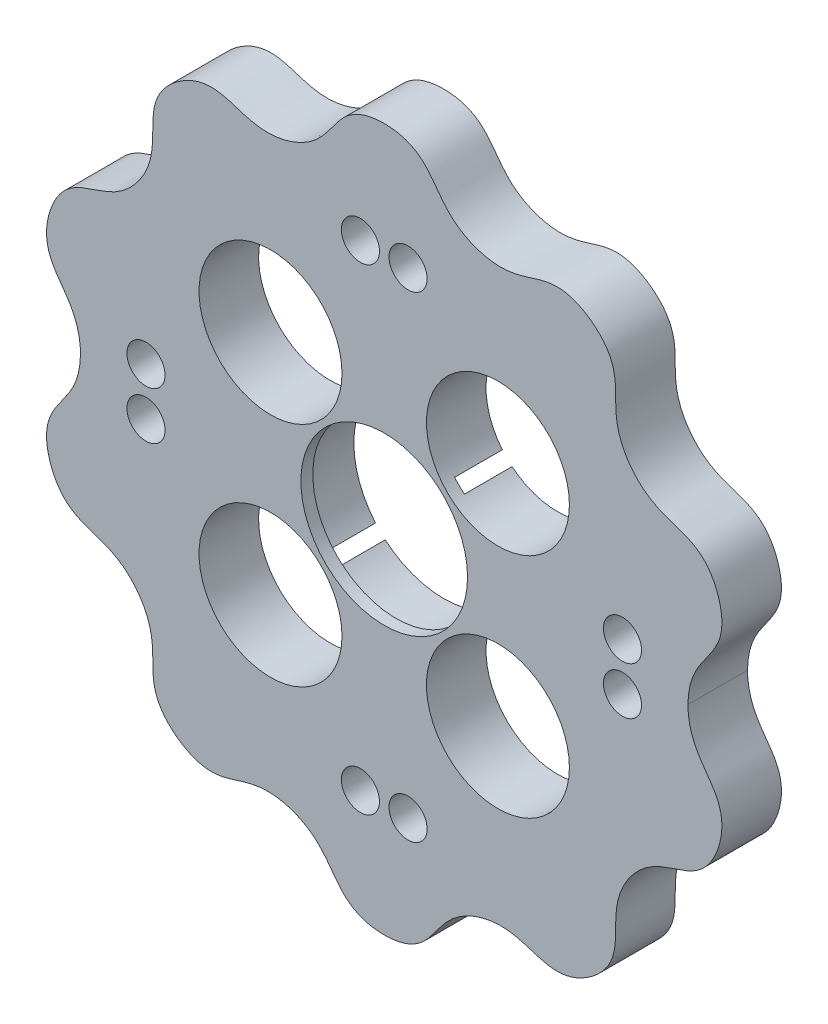
SolidWorks part; units mm, degrees
material "ABS"
ref_plane "Front Plane" through (0, 0, 0) normal (0, 0, 1) x (1, 0, 0)
ref_plane "Top Plane" through (0, 0, 0) normal (0, 1, 0) x (1, 0, 0)
ref_plane "Right Plane" through (0, 0, 0) normal (1, 0, 0) x (0, 0, -1)
ref_plane "Plane1" through (0, 0, 4) normal (0, 0, 1) x (1, 0, 0)
sketch "Sketch3" plane through (0, 0, 4) normal (0, 0, 1) x (1, 0, 0)
  circle A0 centre (2, 0) radius 7.5
  spline S0 degree 5 poles (-23.5, 0) (-23.5, -0.6619) (-23.5985, -1.4561) (-23.8874, -2.4734) (-24.5265, -3.4803) (-25.3239, -4.5428) (-25.7599, -5.1922) (-26.203, -6.107) (-26.3992, -6.9747) (-26.3685, -8.1757) (-26.0322, -9.4106) (-25.4671, -10.5179) (-24.8895, -11.2256) (-23.9802, -11.9083) (-23.1576, -12.2723) (-21.7572, -12.687) (-20.1242, -13.2676) (-18.7699, -14.5833) (-17.7259, -16.1905) (-17.3933, -18.0022) (-17.4393, -19.3418) (-17.4288, -20.3924) (-17.2271, -21.518) (-16.8759, -22.3353) (-16.145, -23.2889) (-15.1471, -24.0902) (-14.0391, -24.6539) (-13.1558, -24.8869) (-12.0189, -24.9048) (-11.1394, -24.7158) (-9.7628, -24.2281) (-8.1004, -23.738) (-6.2314, -24.0063) (-4.442, -24.693) (-3.1081, -25.9632) (-2.3579, -27.074) (-1.7319, -27.9177) (-0.9071, -28.7098) (-0.1425, -29.1646) (1.0093, -29.5065) (2.2876, -29.5682) (3.5153, -29.373) (4.3668, -29.0423) (5.2971, -28.3885) (5.8976, -27.7187) (6.7246, -26.515) (7.7814, -25.1413) (9.4513, -24.2598) (11.3025, -23.7636) (13.1282, -24.0071) (14.3881, -24.4648) (15.3905, -24.7795) (16.5233, -24.9355) (17.4092, -24.854) (18.5419, -24.4536) (19.6124, -23.7522) (20.4909, -22.8726) (20.9855, -22.1045) (21.3538, -21.0288) (21.4458, -20.1339) (21.4074, -18.674) (21.455, -16.9415) (22.2878, -15.2469) (23.4937, -13.7573) (25.1139, -12.8812) (26.4022, -12.5109) (27.3981, -12.1763) (28.4063, -11.6367) (29.0751, -11.05) (29.7562, -10.0602) (30.2099, -8.8636) (30.4037, -7.6356) (30.3523, -6.7236) (30.018, -5.6368) (29.5664, -4.8587) (28.6772, -3.7002) (27.9235, -2.6005) (27.5985, -1.4561) (27.5, -0.6619) (27.5, 0) knots 0.5 0.5 0.5 0.5 0.5 0.5 0.516667 0.52 0.526667 0.53 0.533333 0.536667 0.546667 0.55 0.56 0.563333 0.566667 0.57 0.58 0.583333 0.6 0.61 0.616667 0.626667 0.63 0.633333 0.636667 0.646667 0.65 0.66 0.663333 0.666667 0.67 0.68 0.683333 0.7 0.71 0.716667 0.726667 0.73 0.733333 0.736667 0.746667 0.75 0.76 0.763333 0.766667 0.77 0.78 0.783333 0.8 0.81 0.816667 0.826667 0.83 0.833333 0.836667 0.846667 0.85 0.86 0.863333 0.866667 0.87 0.88 0.883333 0.9 0.91 0.916667 0.926667 0.93 0.933333 0.936667 0.946667 0.95 0.96 0.963333 0.966667 0.97 0.98 0.983333 1 1 1 1 1 1 weights 1 1 1 1 1 1 1 1 1 1 1 1 1 1 1 1 1 1 1 1 1 1 1 1 1 1 1 1 1 1 1 1 1 1 1 1 1 1 1 1 1 1 1 1 1 1 1 1 1 1 1 1 1 1 1 1 1 1 1 1 1 1 1 1 1 1 1 1 1 1 1 1 1 1 1 1 1 1 1 1
  spline S1 degree 5 poles (27.5, 0) (27.5, 0.6619) (27.5985, 1.4561) (27.8874, 2.4734) (28.5265, 3.4803) (29.3239, 4.5428) (29.7599, 5.1922) (30.203, 6.107) (30.3992, 6.9747) (30.3685, 8.1757) (30.0322, 9.4106) (29.4671, 10.5179) (28.8895, 11.2256) (27.9802, 11.9083) (27.1576, 12.2723) (25.7572, 12.687) (24.1242, 13.2676) (22.7699, 14.5833) (21.7259, 16.1905) (21.3933, 18.0022) (21.4393, 19.3418) (21.4288, 20.3924) (21.2271, 21.518) (20.8759, 22.3353) (20.145, 23.2889) (19.1471, 24.0902) (18.0391, 24.6539) (17.1558, 24.8869) (16.0189, 24.9048) (15.1394, 24.7158) (13.7628, 24.2281) (12.1004, 23.738) (10.2314, 24.0063) (8.442, 24.693) (7.1081, 25.9632) (6.3579, 27.074) (5.7319, 27.9177) (4.9071, 28.7098) (4.1425, 29.1646) (2.9907, 29.5065) (1.7124, 29.5682) (0.4847, 29.373) (-0.3668, 29.0423) (-1.2971, 28.3885) (-1.8976, 27.7187) (-2.7246, 26.515) (-3.7814, 25.1413) (-5.4513, 24.2598) (-7.3025, 23.7636) (-9.1282, 24.0071) (-10.3881, 24.4648) (-11.3905, 24.7795) (-12.5233, 24.9355) (-13.4092, 24.854) (-14.5419, 24.4536) (-15.6124, 23.7522) (-16.4909, 22.8726) (-16.9855, 22.1045) (-17.3538, 21.0288) (-17.4458, 20.1339) (-17.4074, 18.674) (-17.455, 16.9415) (-18.2878, 15.2469) (-19.4937, 13.7573) (-21.1139, 12.8812) (-22.4022, 12.5109) (-23.3981, 12.1763) (-24.4063, 11.6367) (-25.0751, 11.05) (-25.7562, 10.0602) (-26.2099, 8.8636) (-26.4037, 7.6356) (-26.3523, 6.7236) (-26.018, 5.6368) (-25.5664, 4.8587) (-24.6772, 3.7002) (-23.9235, 2.6005) (-23.5985, 1.4561) (-23.5, 0.6619) (-23.5, 0) knots 0 0 0 0 0 0 0.016667 0.02 0.026667 0.03 0.033333 0.036667 0.046667 0.05 0.06 0.063333 0.066667 0.07 0.08 0.083333 0.1 0.11 0.116667 0.126667 0.13 0.133333 0.136667 0.146667 0.15 0.16 0.163333 0.166667 0.17 0.18 0.183333 0.2 0.21 0.216667 0.226667 0.23 0.233333 0.236667 0.246667 0.25 0.26 0.263333 0.266667 0.27 0.28 0.283333 0.3 0.31 0.316667 0.326667 0.33 0.333333 0.336667 0.346667 0.35 0.36 0.363333 0.366667 0.37 0.38 0.383333 0.4 0.41 0.416667 0.426667 0.43 0.433333 0.436667 0.446667 0.45 0.46 0.463333 0.466667 0.47 0.48 0.483333 0.5 0.5 0.5 0.5 0.5 0.5 weights 1 1 1 1 1 1 1 1 1 1 1 1 1 1 1 1 1 1 1 1 1 1 1 1 1 1 1 1 1 1 1 1 1 1 1 1 1 1 1 1 1 1 1 1 1 1 1 1 1 1 1 1 1 1 1 1 1 1 1 1 1 1 1 1 1 1 1 1 1 1 1 1 1 1 1 1 1 1 1 1
extrude "CYC Disk" add sketch "Sketch3" along normal blind 5
sketch "Sketch6" plane through (0, 0, 9) normal (0, 0, 1) x (1, 0, 0)
  line L0 (0, 0) -> (2, 0) construction
  circle A1 centre (2, 0) radius 7.55
  dimension "D2" = 15.1
  dimension "D1" = 2
extrude "Cam Bearing" cut sketch "Sketch6" against normal through all
sketch "Sketch8" plane through (0, 0, 9) normal (0, 0, 1) x (1, 0, 0)
  circle A0 centre (2, 0) radius 6.9953
  circle A1 centre (2, 0) radius 7.575
extrude "Cam Bearing Retainer" add sketch "Sketch8" against normal blind 1
sketch "Sketch9" plane through (0, 0, 9) normal (0, 0, 1) x (1, 0, 0)
  line L0 (2, 0) -> (2, 20) construction
  line L2 (4, 20) -> (2, 20)
  line L3 (2, 20) -> (0, 20)
  circle A2 centre (0, 20) radius 1.6
  circle A3 centre (4, 20) radius 1.6
  circle A4 centre (22, -2) radius 1.6
  circle A5 centre (22, 2) radius 1.6
  circle A6 centre (0, -20) radius 1.6
  circle A7 centre (4, -20) radius 1.6
  circle A8 centre (-18, 2) radius 1.6
  circle A9 centre (-18, -2) radius 1.6
  point P23 (2, 0)
  dimension "D3" = 2
  dimension "D4" = 3.2
  dimension "D5" = 3.2
  dimension "D6" = 4
  dimension "D1" = 2
  dimension "D2" = 20
extrude "Positioning Holes" cut sketch "Sketch9" against normal through all
sketch "CYC Ouput Sketch" plane through (2, 0, 4) normal (0, 0, 1) x (1, 0, 0)
  line L1 (9.5459, 9.5459) -> (-9.5459, 9.5459) construction
  line L2 (-9.5459, 9.5459) -> (-9.5459, -9.5459) construction
  line L3 (-9.5459, -9.5459) -> (9.5459, -9.5459) construction
  line L4 (9.5459, -9.5459) -> (9.5459, 9.5459) construction
  circle A0 centre (0, 0) radius 13.5 construction
sketch "Sketch11" plane through (0, 0, 9) normal (0, 0, 1) x (1, 0, 0)
  circle A0 centre (11.5459, 9.5459) radius 6
  circle A1 centre (11.5459, -9.5459) radius 6
  circle A2 centre (-7.5459, -9.5459) radius 6
  circle A3 centre (-7.5459, 9.5459) radius 6
  dimension "D1" = 12
extrude "Output Holes" cut sketch "Sketch11" against normal through all
equation "\"CamBearingOut\"=15.1"
equation "\"D2@Sketch6\"=\"CamBearingOut\""
equation "\"RingPinShaft\"= 5.05"
equation "\"CenterBearingOut\"=32.00"
equation "\"RingPostIn\"=5.15"
